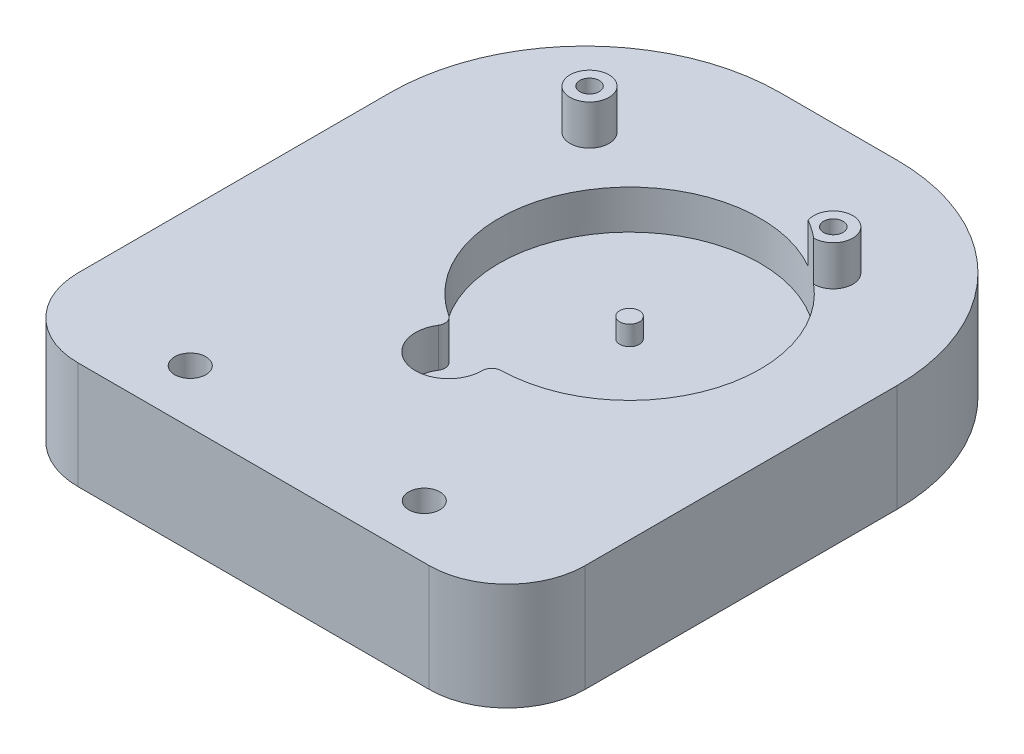
SolidWorks part; units mm, degrees
other "Markup1"
sketch "Sketch1" plane through (0, 0, 0) normal (0.1048, 0.6123, 0.7837) x (0.9942, -0.0832, -0.068)
other "Markup2"
sketch "Sketch2" plane through (0, 0, 0) normal (0.1048, 0.6123, 0.7837) x (0.9942, -0.0832, -0.068)
material "ABS"
ref_plane "Plan de face" through (0, 0, 0) normal (0, 0, 1) x (1, 0, 0)
ref_plane "Plan de dessus" through (0, 0, 0) normal (0, 1, 0) x (1, 0, 0)
ref_plane "Plan de droite" through (0, 0, 0) normal (1, 0, 0) x (0, 0, -1)
sketch "Sketch3" plane through (0, 0, 0) normal (0, 1, 0) x (1, 0, 0)
  line L1 (-13, -15) -> (13, -15)
  line L2 (-13, -15) -> (-13, 15)
  line L3 (-13, 15) -> (13, 15)
  line L4 (13, -15) -> (13, 15)
  line L5 (-13, -15) -> (13, 15) construction
  line L6 (-13, 15) -> (13, -15) construction
  point P0 (0, 0)
  dimension "D1" = 26
  dimension "D2" = 30
extrude "Boss-Extrude1" add sketch "Sketch3" along normal blind 3
sketch "Sketch4" plane through (0, 3, 0) normal (0, 1, 0) x (1, 0, 0)
  line L0 (-13, -15) -> (13, -15) construction
  line L1 (-13, 15) -> (-13, -15) construction
  line L2 (0, -5) -> (2.0673, 2.2095) construction
  line L3 (2.0673, 2.2095) -> (6.3691, 8.3531) construction
  line L4 (6.3691, 8.3531) -> (-6.1309, 8.3531) construction
  line L5 (0, -5) -> (0, -4.025) construction
  line L6 (13, -15) -> (13, 15) construction
  circle A0 centre (0, -5) radius 4
  circle A1 centre (2.0673, 2.2095) radius 0.5
  circle A2 centre (6.3691, 8.3531) radius 0.5
  circle A3 centre (-6.1309, 8.3531) radius 0.5
  dimension "D1" = 8
  dimension "D5" = 1
  dimension "D8" = 1
  dimension "D11" = 6.8691
  dimension "D12" = 6.6309
  dimension "D2" = 10
  dimension "D3" = 13
  dimension "D4" = 7.5
  dimension "D6" = 12.5
  dimension "D7" = 7.5
  dimension "D9" = 16
  dimension "D10" = 35
extrude "Cut-Extrude1" cut sketch "Sketch4" against normal through all
sketch "Sketch5" plane through (0, 3, 0) normal (0, 1, 0) x (1, 0, 0)
  line L0 (13, 15) -> (-13, 15) construction
  line L11 (0, -15) -> (-13, -15)
  line L12 (-13, -11) -> (-13, -15)
  line L15 (0, -15) -> (13, -15)
  line L16 (13, -18.5) -> (13, -15)
  line L17 (-13, -15) -> (-10.0581, -15)
  line L18 (-13, -15) -> (-13, 15)
  line L19 (-13, 15) -> (-10.0581, 15)
  line L20 (-9.1309, -9.5) -> (-9.1309, 10.3531)
  line L22 (13, -15) -> (10.0242, -15)
  line L23 (13, -15) -> (13, 15)
  line L24 (13, 15) -> (10.0242, 15)
  line L25 (9.3691, -9.5) -> (9.3691, 10.3531)
  line L26 (-13, 15) -> (13, 15)
  line L27 (-13, 15) -> (-13, 0)
  line L28 (-9.1309, 10.3531) -> (9.3691, 10.3531)
  line L29 (13, 15) -> (13, 0)
  line L31 (-9.1309, -9.5) -> (9.3691, -9.5)
  circle A0 centre (-6.1309, 8.3531) radius 0.5 construction
  circle A2 centre (6.3691, 8.3531) radius 0.5 construction
  dimension "D3" = 3
  dimension "D1" = 4
  dimension "D2" = 3
  dimension "D4" = 2
  dimension "D5" = 5.5
extrude "Boss-Extrude2" add sketch "Sketch5" along normal blind 2.5
fillet "Fillet2" radius 10 1 edges at (-13, 2.75, -15)
fillet "Fillet3" radius 10 1 edges at (13, 2.75, -15)
fillet "Fillet10" radius 4 1 edges at (-13, 2.75, 15)
fillet "Fillet11" radius 4 1 edges at (13, 2.75, 15)
hole_wizard "M2 Tapped Hole1" positions "Sketch6" profile "Sketch7" tap size "M2" standard "ISO" end condition up to next
sketch "Sketch6" plane through (0, 5.5, 0) normal (0, 1, 0) x (1, 0, 0)
  point P0 (-6, -12.25)
  point P2 (6, -12.25)
  dimension "D1" = 12
  dimension "D2" = 7
  dimension "D3" = 7
  dimension "D4" = 2.75
  dimension "D5" = 2.75
sketch "Sketch7" plane through (-6, 5.5, 12.25) normal (1, 0, 0) x (0, 0, 1)
  line L0 (0, 0) -> (0, 5.5)
  line L1 (0, 5.5) -> (0.8, 5.5)
  line L2 (0.8, 5.5) -> (0.8, 0)
  line L5 (0.8, 0) -> (0, 0)
  line L11 (0, -6.35) -> (0, 107.95) construction
  dimension "Thru Tap Drill Dia." = 1.6
  dimension "Thru Tap Drill Depth" = 5.5
cosmetic thread "Hole Thread1" parameters "D2"=2
cosmetic thread "Hole Thread2" parameters "D2"=2
sketch "Sketch10" plane through (0, 3, 0) normal (0, 1, 0) x (1, 0, 0)
  line L1 (-9.1309, 10.3531) -> (9.3691, 10.3531)
  line L2 (-9.1309, 10.3531) -> (-9.1309, -9.5)
  line L3 (-9.1309, -9.5) -> (9.3691, -9.5)
  line L4 (9.3691, 10.3531) -> (9.3691, -9.5)
extrude "Boss-Extrude3" add sketch "Sketch10" along normal blind 0.5
sketch "Sketch14" plane through (0, 3.5, 0) normal (0, 1, 0) x (1, 0, 0)
  line L0 (0, -5) -> (2.0673, 2.2095) construction
  line L1 (2.0673, 2.2095) -> (6.3691, 8.3531) construction
  line L2 (6.3691, 8.3531) -> (-6.1309, 8.3531) construction
  line L3 (0, -5) -> (0, -4.025) construction
  line L4 (2.0673, 2.2095) -> (6.3691, 8.3531) construction
  circle A0 centre (0, -5) radius 0.5
  circle A1 centre (2.0673, 2.2095) radius 0.5
  circle A2 centre (6.3691, 8.3531) radius 0.5
  circle A3 centre (-6.1309, 8.3531) radius 0.5
  dimension "D3" = 0
  dimension "D4" = 1
extrude "Cut-Extrude2" cut sketch "Sketch14" against normal blind 0.5
sketch "Sketch15" plane through (0, 3.5, 0) normal (0, 1, 0) x (1, 0, 0)
  line L4 (-9.1309, 10.3531) -> (-9.1309, -9.5)
  line L5 (-9.1309, -9.5) -> (9.3691, -9.5)
  line L6 (9.3691, -9.5) -> (9.3691, 10.3531)
  line L7 (9.3691, 10.3531) -> (-9.1309, 10.3531)
  line L8 (-9.1309, 10.3531) -> (-9.1309, -9.5)
  line L9 (-9.1309, -9.5) -> (9.3691, -9.5)
  line L10 (9.3691, -9.5) -> (9.3691, 10.3531)
  line L11 (9.3691, 10.3531) -> (-9.1309, 10.3531)
  arc A0 (-1.0933, -3.6982) -> (1.617, -4.4754) centre (0, -5) ccw
  arc A1 (1.617, -4.4754) -> (-1.0933, -3.6982) centre (2.0673, 2.2095) ccw
  circle A4 centre (6.3691, 8.3531) radius 0.5
  circle A5 centre (-6.1309, 8.3531) radius 0.5
  dimension "D2" = 13.4
  dimension "D3" = 3.4
  dimension "D1" = 0
extrude "Boss-Extrude4" add sketch "Sketch15" along normal up to surface (2 mm away)
sketch "Sketch16" plane through (0, 5.5, 0) normal (0, 1, 0) x (1, 0, 0)
  circle A0 centre (-6.1309, 8.3531) radius 0.5 construction
  circle A1 centre (-6.1309, 8.3531) radius 0.5
  circle A2 centre (6.3691, 8.3531) radius 0.5 construction
  circle A3 centre (6.3691, 8.3531) radius 0.5
  circle A4 centre (-6.1309, 8.3531) radius 1
  arc A5 (6.3606, 7.3531) -> (5.4324, 8.0031) centre (6.3691, 8.3531) ccw
  arc A6 (1.617, -4.4754) -> (-1.0933, -3.6982) centre (2.0673, 2.2095) ccw construction
  arc A7 (6.3606, 7.3531) -> (5.4324, 8.0031) centre (2.0673, 2.2095) ccw
  dimension "D1" = 2
  dimension "D2" = 2
extrude "Boss-Extrude5" add sketch "Sketch16" along normal blind 2.05
sketch "Sketch17" plane through (0, 0, 0) normal (0, -1, 0) x (1, 0, 0)
  circle A0 centre (2.0673, -2.2095) radius 0.5
extrude "Boss-Extrude6" add sketch "Sketch17" against normal blind 4.5
fillet "Fillet12" radius 0.5 2 edges at (1.617, 4.5, 4.4754) (-1.0933, 4.5, 3.6982)
sketch "Sketch18" plane through (0, 5.5, 0) normal (0, 1, 0) x (1, 0, 0)
  circle A0 centre (-8.4688, -1.9225) radius 3.4472
  circle A1 centre (7.4174, -7.3326) radius 2.8746
extrude "Cut-Extrude3" [suppressed] cut sketch "Sketch18" against normal through all
sketch "Sketch19" plane through (0, 0, 0) normal (0, -1, 0) x (1, 0, 0)
  line L2 (0, 5) -> (-7.7697, 5) construction
  line L4 (-4.7697, 6.5) -> (-7.7697, 6.5)
  line L5 (-7.7697, 6.5) -> (-7.7697, 3.5)
  line L6 (-4.7697, 3.5) -> (-7.7697, 3.5)
  circle A0 centre (0, 5) radius 4
  arc A1 (-4.7697, 3.5) -> (-4.7697, 6.5) centre (0, 5) ccw
  circle A2 centre (0, 5) radius 4 construction
  dimension "D1" = 1
  dimension "D2" = 3
  dimension "D3" = 3
extrude "Boss-Extrude7" add sketch "Sketch19" along normal blind 4
sketch "Sketch21" plane through (-7.7697, 0, 0) normal (-1, 0, 0) x (0, 0, 1)
  line L0 (0, 0) -> (0, -4) construction
  line L1 (10, 0) -> (0, 0)
  line L2 (10, 0) -> (10, -1)
  line L3 (10, -1) -> (0, -1)
  line L4 (0, 0) -> (0, -1)
  dimension "D1" = 1
extrude "Cut-Extrude5" cut sketch "Sketch21" against normal blind 11
sketch "Sketch22" plane through (0, 0, 3.5) normal (0, 0, -1) x (-1, 0, 0)
  line L0 (7.7697, -2.5) -> (6.5197, -2.5) construction
  line L1 (7.7697, -4) -> (7.7697, -1) construction
  circle A0 centre (6.5197, -2.5) radius 1
  dimension "D2" = 2
  dimension "D1" = 1.25
extrude "Cut-Extrude6" cut sketch "Sketch22" against normal through all
sketch "Sketch24" plane through (0, -4, 0) normal (0, -1, 0) x (1, 0, 0)
  line L0 (-7.7697, 6.5) -> (-7.7697, 3.5) construction
  line L1 (-7.7697, 5.5) -> (-3.9686, 5.5)
  line L2 (-7.7697, 5.5) -> (-7.7697, 4.5)
  line L3 (-7.7697, 4.5) -> (-3.9686, 4.5)
  line L4 (-3.9686, 5.5) -> (-3.9686, 4.5)
  line L5 (0, 5) -> (-3.9686, 5) construction
  circle A0 centre (0, 5) radius 4 construction
  dimension "D1" = 1
extrude "Cut-Extrude7" cut sketch "Sketch24" against normal up to vertex (3 mm away) up to point (-7.7697, -1, 3.5)
